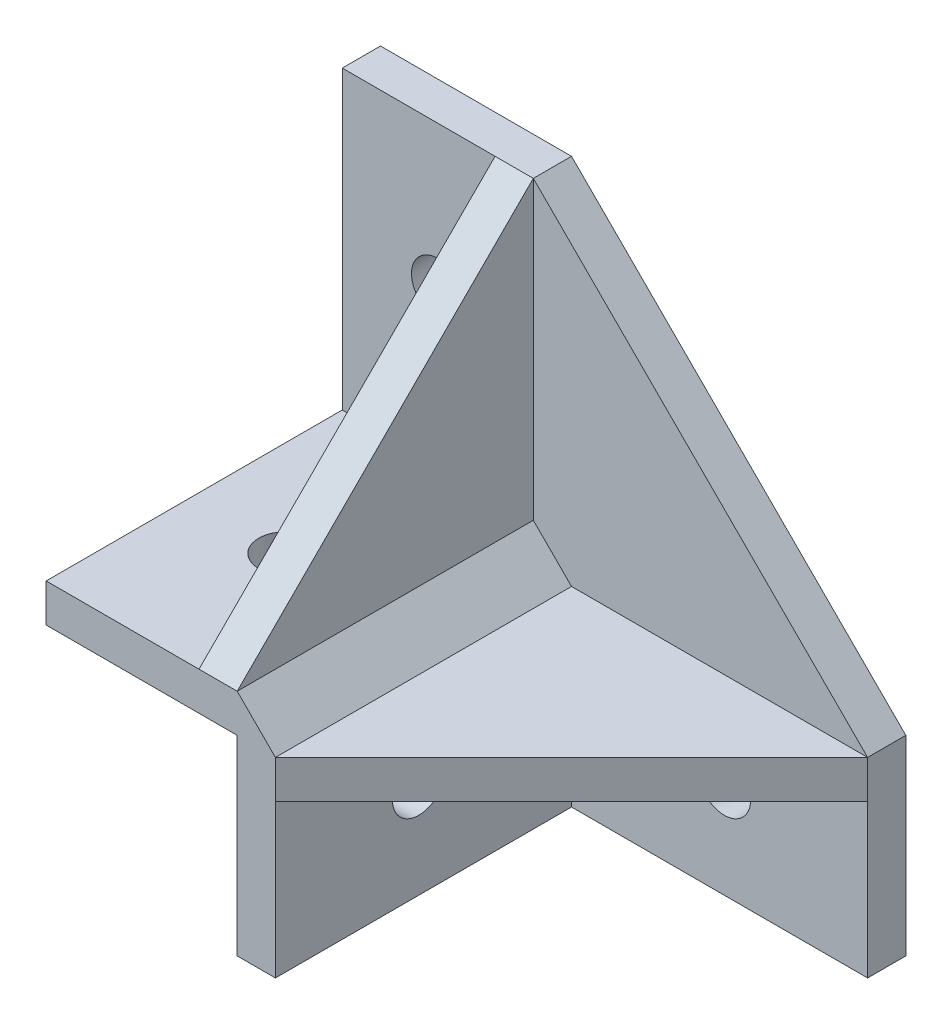
SolidWorks part; units mm, degrees
ref_plane "Front" through (0, 0, 0) normal (0, 0, 1) x (1, 0, 0)
ref_plane "Top" through (0, 0, 0) normal (0, 1, 0) x (1, 0, 0)
ref_plane "Right" through (0, 0, 0) normal (1, 0, 0) x (0, 0, -1)
sketch "Sketch1" plane through (0, 0, 0) normal (0, 0, 1) x (1, 0, 0)
  line L0 (0, 35) -> (35, 0)
  line L1 (-20, 35) -> (0, 35)
  line L2 (-20, 35) -> (-20, 0)
  line L3 (-20, 0) -> (0, 0)
  line L4 (0, 35) -> (0, 0) construction
  line L5 (0, 0) -> (35, 0) construction
  line L6 (0, 0) -> (0, -20)
  line L7 (0, -20) -> (35, -20)
  line L8 (35, 0) -> (35, -20)
  dimension "D1" = 20
  dimension "D2" = 35
extrude "Boss-Extrude1" add sketch "Sketch1" along normal blind 4
sketch "Sketch2" plane through (0, 0, 4) normal (0, 0, 1) x (1, 0, 0)
  line L0 (-20, 0) -> (0, 0)
  line L1 (0, 0) -> (0, -20)
  line L2 (-20, 0) -> (-20, 4)
  line L3 (-20, 4) -> (-4, 4)
  line L4 (0, -20) -> (4, -20)
  line L5 (0, 35) -> (-4, 35)
  line L6 (0, -20) -> (35, -20) construction
  line L7 (4, -20) -> (4, -4)
  line L8 (-4, 35) -> (-4, 4)
  line L9 (4, -4) -> (35, -4)
  line L10 (35, -20) -> (35, 0) construction
  line L11 (35, -4) -> (35, 0)
  line L12 (35, 0) -> (4, 0)
  line L13 (4, 0) -> (0, 4)
  line L14 (0, 4) -> (0, 35)
  dimension "D1" = 4
extrude "Boss-Extrude2" add sketch "Sketch2" along normal blind 31
chamfer "Chamfer2" distance 31 angle 45 2 edges at (-2, 35, 35) (35, -2, 35)
sketch "Sketch3" plane through (0, 0, 0) normal (0, 0, -1) x (-1, 0, 0)
  line L0 (10, 20) -> (10, -10) construction
  line L1 (10, -10) -> (-20, -10) construction
  line L4 (20, 0) -> (0, 0) construction
  line L5 (0, 0) -> (0, -20) construction
  circle A0 centre (10, 20) radius 2.75
  circle A1 centre (-20, -10) radius 2.75
  point P6 (10, 0)
  point P7 (0, -10)
  dimension "D2" = 5.5
  dimension "D1" = 30
extrude "Cut-Extrude1" cut sketch "Sketch3" against normal up to next
sketch "Sketch4" plane through (0, 0, 0) normal (0, -1, 0) x (1, 0, 0)
  line L2 (-20, 0) -> (0, 0) construction
  circle A0 centre (-10, 20) radius 2.75
  point P5 (-10, 0)
  dimension "D2" = 5.5
  dimension "D1" = 20
extrude "Cut-Extrude2" cut sketch "Sketch4" against normal up to next
sketch "Sketch5" plane through (0, 0, 0) normal (-1, 0, 0) x (0, 0, 1)
  line L1 (0, 0) -> (0, -20) construction
  circle A0 centre (20, -10) radius 2.75
  point P5 (0, -10)
  dimension "D1" = 5.5
  dimension "D2" = 20
extrude "Cut-Extrude3" cut sketch "Sketch5" against normal up to next
